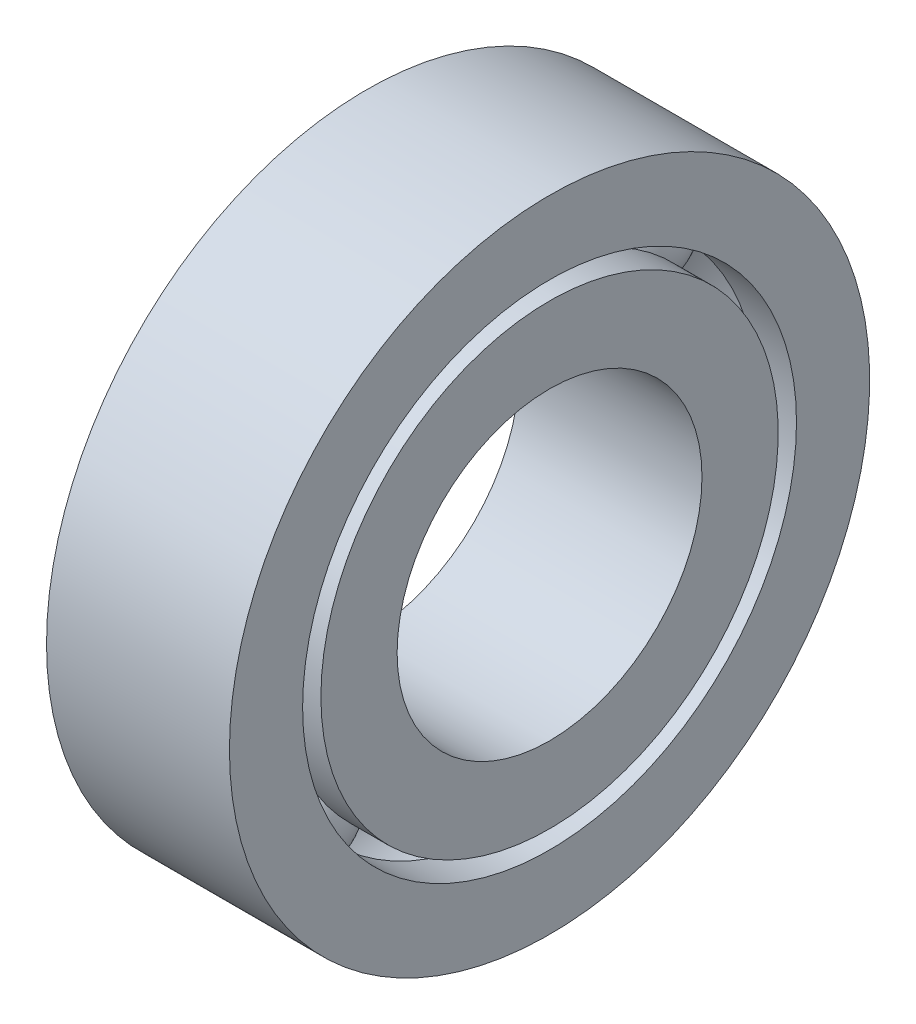
SolidWorks part; units mm, degrees
material "1.0037 (S235JR)"
ref_plane "Ön Düzlem" through (0, 0, 0) normal (0, 0, 1) x (1, 0, 0)
ref_plane "Üst Düzlem" through (0, 0, 0) normal (0, 1, 0) x (1, 0, 0)
ref_plane "Sağ Düzlem" through (0, 0, 0) normal (1, 0, 0) x (0, 0, -1)
sketch "Çizim1" plane through (0, 0, 0) normal (0, 0, 1) x (1, 0, 0)
  line L0 (0, 21) -> (0, 16.2)
  line L1 (0, 10) -> (12, 10)
  line L2 (0, 10) -> (0, 15)
  line L3 (0, 15) -> (2.5518, 15)
  line L4 (12, 10) -> (12, 15)
  line L5 (0, 21) -> (12, 21)
  line L9 (0, 16.2) -> (2.5518, 16.2)
  line L10 (12, 16.2) -> (12, 21)
  line L11 (6, 16.2) -> (6, 15) construction
  line L12 (9.4482, 16.2) -> (12, 16.2)
  line L13 (9.4482, 15) -> (12, 15)
  line L14 (0, 0) -> (12, 0) construction
  arc A0 (2.5518, 15) -> (9.4482, 15) centre (6, 15.6) ccw
  arc A1 (9.4482, 16.2) -> (2.5518, 16.2) centre (6, 15.6) ccw
  dimension "D5" = 7
  dimension "D1" = 10
  dimension "D2" = 21
  dimension "D3" = 12
  dimension "D4" = 5
  dimension "D6" = 1.2
revolve "Döndür1" add sketch "Çizim1" angle 360 about L14
sketch "Çizim2" plane through (0, 0, 0) normal (0, 0, 1) x (1, 0, 0)
  line L0 (0, 16.2) -> (0, 15) construction
  line L1 (0, 21) -> (0, -21) construction
  line L2 (0, 16.2) -> (0, -16.2) construction
  line L3 (0, 15) -> (0, -15) construction
  line L4 (12, 16.2) -> (12, 15) construction
  line L5 (12, -16.2) -> (12, 16.2) construction
  line L6 (12, -15) -> (12, 15) construction
  line L7 (12, -21) -> (12, 21) construction
  line L8 (0, 15.6) -> (12, 15.6) construction
  line L9 (2.6, 15.6) -> (9.4, 15.6)
  arc A0 (9.4, 15.6) -> (2.6, 15.6) centre (6, 15.6) ccw
  dimension "D1" = 6.8
revolve "Döndür2" add sketch "Çizim2" angle 360 about L9
pattern_circular "Dairesel Kaplama9" count 8 over 360 about axis through (0, 0, 0) along (1, 0, 0) of bodies 103
